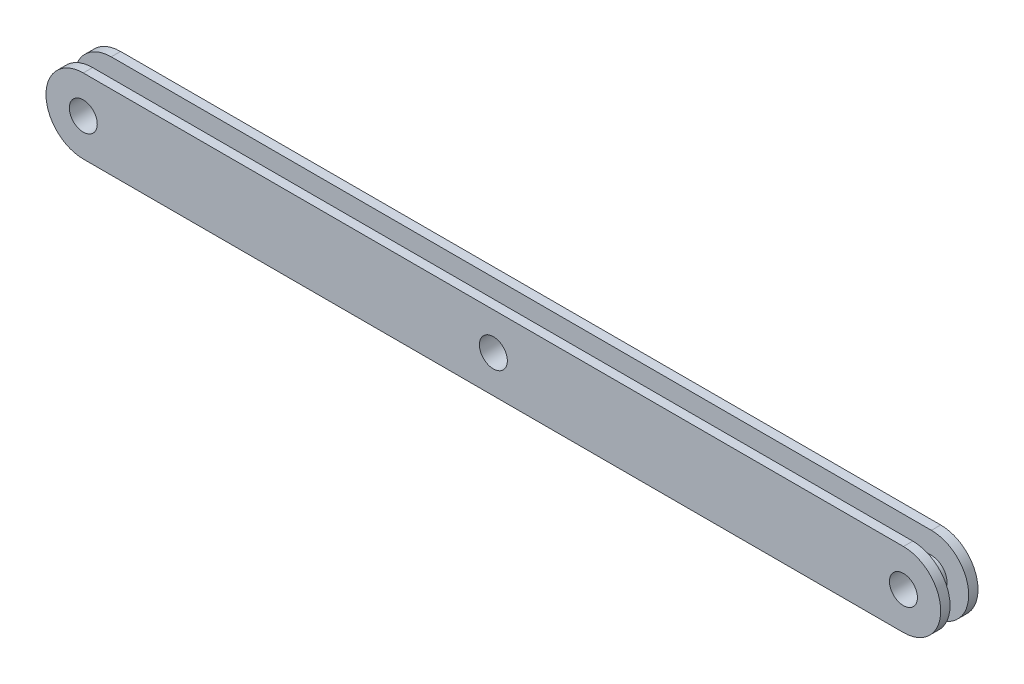
SolidWorks part; units mm, degrees
ref_plane "Plan de face" through (0, 0, 0) normal (0, 0, 1) x (1, 0, 0)
ref_plane "Plan de dessus" through (0, 0, 0) normal (0, 1, 0) x (1, 0, 0)
ref_plane "Plan de droite" through (0, 0, 0) normal (1, 0, 0) x (0, 0, -1)
sketch "Esquisse1" plane through (0, 0, 0) normal (0, 0, 1) x (1, 0, 0)
  line L4 (0, 0) -> (-152.4, 0)
  line L5 (-152.4, 0) -> (-152.4, 12.7)
  line L6 (-152.4, 12.7) -> (0, 12.7)
  line L7 (0, 12.7) -> (0, 0)
  dimension "D1" = 12.7
  dimension "D2" = 152.4
extrude "Boss.-Extru.1" add sketch "Esquisse1" against normal blind 6.35
sketch "Esquisse2" plane through (0, 0, 0) normal (0, 0, 1) x (1, 0, 0)
  line L0 (0, 12.7) -> (-152.4, 12.7) construction
  line L1 (-152.4, 0) -> (0, 0) construction
  line L2 (-152.4, 12.7) -> (-152.4, 0) construction
  line L3 (-6.35, 12.7) -> (0, 12.7)
  line L4 (0, 12.7) -> (0, 0)
  line L5 (0, 0) -> (0, 12.7) construction
  line L6 (0, 0) -> (-6.35, 0)
  line L7 (-146.05, 12.7) -> (-152.4, 12.7)
  line L8 (-152.4, 12.7) -> (-152.4, 0)
  line L9 (-152.4, 0) -> (-146.05, 0)
  circle A0 centre (-146.05, 6.35) radius 2.3813
  circle A1 centre (-6.35, 6.35) radius 2.3813
  circle A2 centre (-76.2, 6.35) radius 2.3813
  arc A3 (-146.05, 12.7) -> (-146.05, 0) centre (-146.05, 6.35) ccw
  arc A4 (-6.35, 12.7) -> (-6.35, 0) centre (-6.35, 6.35) cw
  line M1 (0, 0) -> (0, 12.7)
  line M2 (0, 12.7) -> (-152.4, 12.7)
  line M3 (-152.4, 12.7) -> (-152.4, 0)
  line M4 (-152.4, 0) -> (0, 0)
  dimension "D1" = 4.7625
  dimension "D4" = 4.7625
  dimension "D7" = 4.7625
  dimension "D2" = 6.35
  dimension "D3" = 6.35
  dimension "D5" = 6.35
  dimension "D6" = 6.35
  dimension "D8" = 69.85
extrude "Enlèv. mat.-Extru.1" cut sketch "Esquisse2" against normal through all contours A0 | A2 | A1 | A4 L4 M2 | A4 M1 M4 | A3 M2 M3 | A3 L8 M4
ref_plane "Plane1" through (0, 0, -3.175) normal (0, 0, 1) x (1, 0, 0)
ref_plane "Plane2" through (0, 6.35, 0) normal (0, 1, 0) x (1, 0, 0)
sketch "Sketch1" plane through (0, 6.35, 0) normal (0, 1, 0) x (1, 0, 0)
  line L0 (-146.05, 6.35) -> (-146.05, 0) construction
  line L1 (-6.35, 6.35) -> (-146.05, 6.35) construction
  line L2 (-6.35, 0) -> (-146.05, 0) construction
  line L3 (-146.05, 6.35) -> (-146.05, 0) construction
  line L4 (-148.4313, 6.35) -> (-148.4313, 0) construction
  line L5 (-146.05, 6.35) -> (-152.4, 6.35) construction
  line L6 (-152.4, 0) -> (-146.05, 0) construction
  line L7 (-152.4, 4.7625) -> (-150.5585, 4.7625)
  line L8 (-152.4, 6.35) -> (-152.4, 0) construction
  line L11 (-148.717, 4.7625) -> (-148.717, 1.5875)
  line L14 (-150.5585, 1.5875) -> (-152.4, 1.5875)
  line L15 (-152.4, 1.5875) -> (-152.4, 4.7625)
  line L16 (-150.5585, 4.7625) -> (-148.717, 4.7625)
  line L17 (-150.5585, 1.5875) -> (-148.717, 1.5875)
  line L18 (-152.4, 4.7625) -> (-166.5708, 4.7625)
  line L19 (-166.5708, 4.7625) -> (-166.5708, 1.5875)
  line L20 (-166.5708, 1.5875) -> (-152.4, 1.5875)
  dimension "D1" = 2.3812
  dimension "D2" = 3.175
  dimension "D3" = 1.5875
  dimension "D4" = 14.1708
  dimension "D5" = 1.8415
revolve "Cut-Revolve1" cut sketch "Sketch1" angle 180 mid plane about L0
ref_plane "Plane3" through (-76.2, 0, 0) normal (1, 0, 0) x (0, 0, -1)
mirror "Mirror1" about plane through (-76.2, 0, 0) normal (1, 0, 0) of "Cut-Revolve1"
sketch "Sketch2" plane through (0, 0, 0) normal (1, 0, 0) x (0, 0, -1)
  line L0 (1.5875, 9.017) -> (1.5875, 12.7) construction
  line L1 (1.5875, 9.017) -> (4.7625, 9.017)
  line L2 (1.5875, 9.017) -> (1.5875, 12.7)
  line L3 (1.5875, 12.7) -> (4.7625, 12.7)
  line L4 (4.7625, 9.017) -> (4.7625, 12.7)
  line L5 (4.7625, 12.7) -> (4.7625, 9.017) construction
  line L6 (4.7625, 12.7) -> (1.5875, 12.7) construction
  line L7 (4.7625, 9.017) -> (1.5875, 9.017) construction
extrude "Cut-Extrude1" cut sketch "Sketch2" against normal through all
mirror "Mirror2" about plane through (0, 6.35, 0) normal (0, 1, 0) of "Cut-Extrude1"
